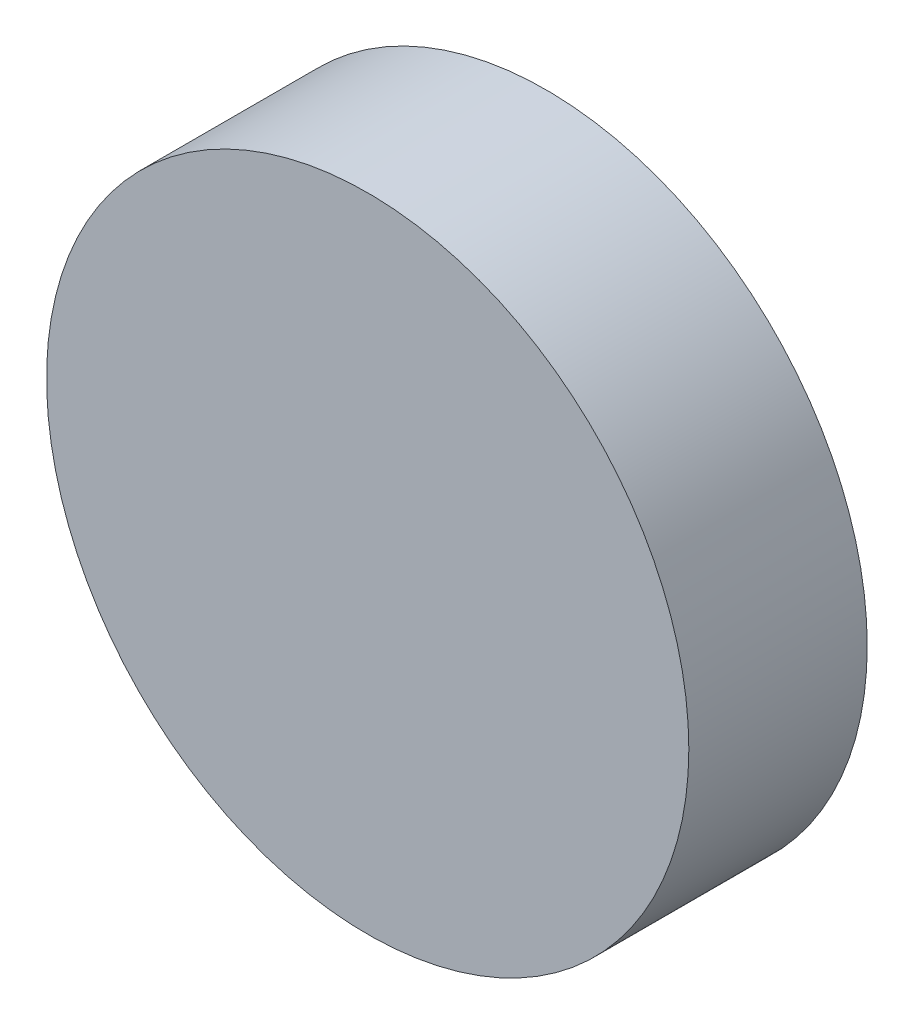
SolidWorks part; units mm, degrees
ref_plane "Front Plane" through (0, 0, 0) normal (0, 0, 1) x (1, 0, 0)
ref_plane "Top Plane" through (0, 0, 0) normal (0, 1, 0) x (1, 0, 0)
ref_plane "Right Plane" through (0, 0, 0) normal (1, 0, 0) x (0, 0, -1)
sketch "Sketch1" plane through (0, 0, 0) normal (0, 0, 1) x (1, 0, 0)
  circle A0 centre (0, 0) radius 9
  dimension "D1" = 18
extrude "Boss-Extrude1" add sketch "Sketch1" along normal blind 5
